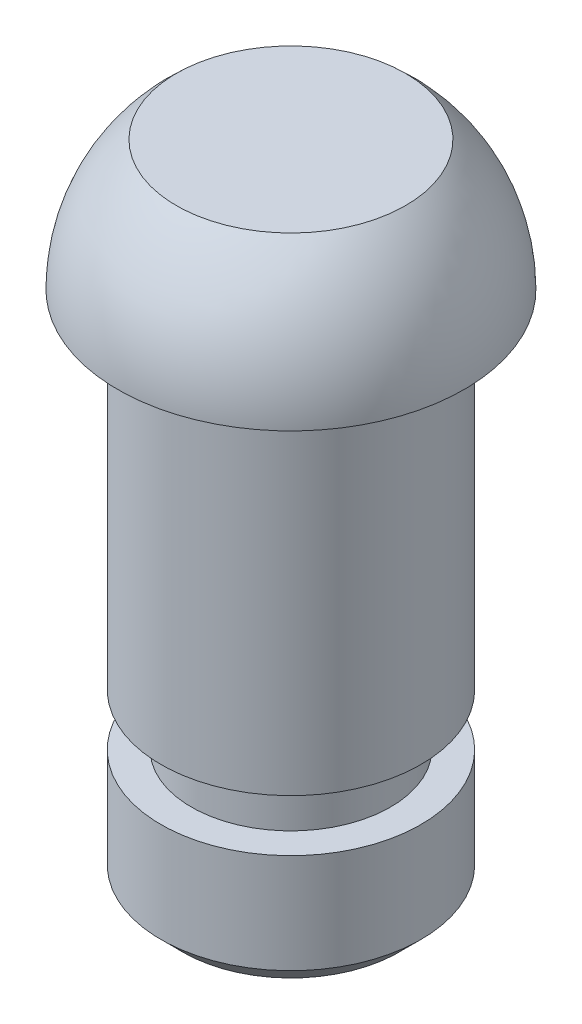
SolidWorks part; units mm, degrees
ref_plane "Front Plane" through (0, 0, 0) normal (0, 0, 1) x (1, 0, 0)
ref_plane "Top Plane" through (0, 0, 0) normal (0, 1, 0) x (1, 0, 0)
ref_plane "Right Plane" through (0, 0, 0) normal (1, 0, 0) x (0, 0, -1)
sketch "Sketch1" plane through (0, 0, 0) normal (0, 0, 1) x (1, 0, 0)
  line L0 (0, 0) -> (0, 6)
  line L2 (1.5, 6) -> (1.5, 2)
  line L3 (1.5, 2) -> (1.15, 2)
  line L4 (1.15, 2) -> (1.15, 1.4)
  line L5 (1.15, 1.4) -> (1.5, 1.4)
  line L6 (1.5, 1.4) -> (1.5, 0)
  line L7 (1.5, 0) -> (0, 0)
  line L8 (1.5, 6) -> (2, 6)
  line L9 (0, 7.5) -> (1.3229, 7.5)
  line L10 (0, 6) -> (0, 7.5)
  arc A0 (2, 6) -> (1.3229, 7.5) centre (0, 6) ccw
  dimension "D6" = 4
  dimension "D1" = 6
  dimension "D2" = 1.5
  dimension "D3" = 4
  dimension "D4" = 1.4
  dimension "D5" = 1.15
  dimension "D7" = 7.5
revolve "Revolve1" add sketch "Sketch1" angle 360 about L0
chamfer "Chamfer1" distance 0.25 angle 45 1 edges at (0, 0, -1.5)
